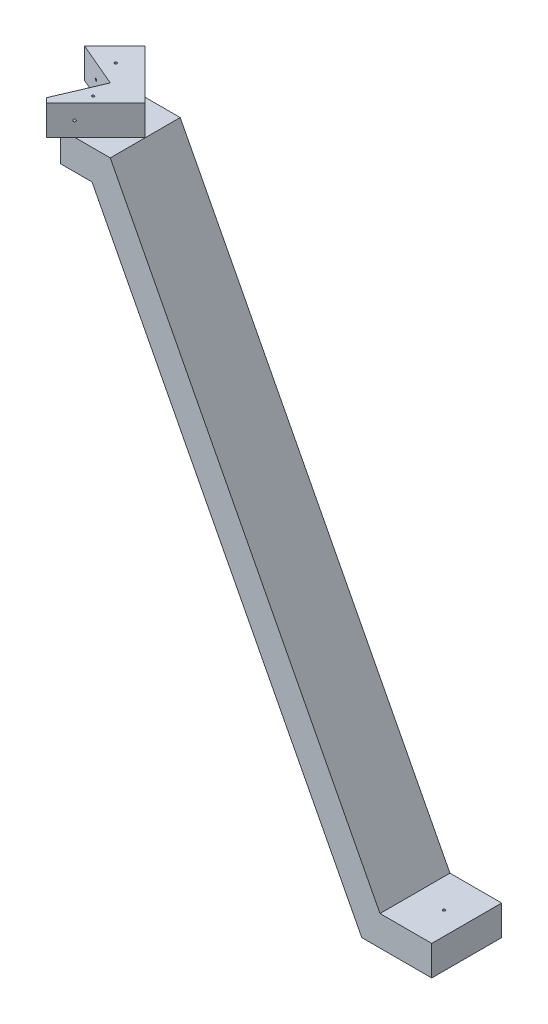
SolidWorks part; units mm, degrees
ref_plane "Frontal Plane" through (0, 0, 0) normal (0, 0, 1) x (1, 0, 0)
ref_plane "Horizontal Plane" through (0, 0, 0) normal (0, 1, 0) x (1, 0, 0)
ref_plane "Profile Plane" through (0, 0, 0) normal (1, 0, 0) x (0, 0, -1)
sketch "Sketch1" plane through (0, 0, 0) normal (0, 0, 1) x (1, 0, 0)
  line L0 (0, 0) -> (-342.9, 660.4)
  line L2 (-319.7529, 698.5) -> (23.1471, 38.1)
  line L3 (23.1471, 38.1) -> (88.9, 38.1)
  line L4 (88.9, 38.1) -> (88.9, 0)
  line L5 (88.9, 0) -> (0, 0)
  line L6 (-319.7529, 698.5) -> (-408.6529, 698.5)
  line L7 (-408.6529, 698.5) -> (-408.6529, 660.4)
  line L8 (-408.6529, 660.4) -> (-342.9, 660.4)
  dimension "D1" = 38.1
  dimension "D2" = 88.9
  dimension "D3" = 431.8
  dimension "D4" = 698.5
  dimension "D5" = 88.9
  dimension "D6" = 38.1
extrude "Boss-Extrude1" add sketch "Sketch1" along normal mid plane 88.9
hole_wizard "1/8 (0.125) Diameter Hole1" positions "3DSketch1" profile "Sketch3" hole size "1/8" standard "ANSI Inch" end condition through all
sketch3d "3DSketch1"
  line L0 (88.9, 38.1, -44.45) -> (23.1471, 38.1, -44.45) construction
  line L1 (88.9, 38.1, 44.45) -> (88.9, 38.1, -44.45) construction
  point P0 (60.1472, 38.1, 0)
  dimension "D1" = 44.45
  dimension "D2" = 28.7528
sketch "Sketch3" plane through (60.1472, 38.1, 0) normal (1, 0, 0) x (0, 0, 1)
  line L0 (0, 0) -> (0, 38.1)
  line L1 (0, 38.1) -> (1.5875, 38.1)
  line L2 (1.5875, 38.1) -> (1.5875, 0)
  line L5 (1.5875, 0) -> (0, 0)
  line L11 (0, -6.35) -> (0, 107.95) construction
  dimension "Thru Hole Dia." = 3.175
  dimension "Thru Hole Depth" = 38.1
sketch "Sketch4" plane through (0, 698.5, 0) normal (0, 1, 0) x (1, 0, 0)
  line L0 (-382.6147, 62.8618) -> (-319.7529, 0)
  line L1 (-319.7529, 0) -> (-382.6147, -62.8618)
  line L3 (-382.6147, -62.8618) -> (-445.4765, 0)
  line L4 (-445.4765, 0) -> (-382.6147, 62.8618)
  line L7 (-319.7529, 44.45) -> (-408.6529, 44.45) construction
  line L8 (-408.6529, -44.45) -> (-408.6529, 44.45) construction
  dimension "D1" = 90
  dimension "D3" = 88.9
  dimension "D4" = 44.45
  dimension "D5" = 88.9
extrude "Boss-Extrude2" add sketch "Sketch4" along normal blind 38.1
sketch "Sketch6" plane through (0, 660.4, 0) normal (0, -1, 0) x (1, 0, 0)
  line L0 (-445.4765, 190.3683) -> (-364.2029, 0)
  line L1 (-364.2029, 0) -> (-445.4765, -34.698)
  line L5 (-408.6529, 36.8236) -> (-408.6529, -36.8236) construction
  line L6 (-445.4765, 190.3683) -> (-445.4765, -34.698)
  line L7 (-408.6529, -44.45) -> (-342.9, -44.45) construction
  line L9 (-364.2029, 0) -> (-479.6244, 0) construction
  dimension "D1" = 44.45
  dimension "D2" = 44.45
  dimension "D3" = 23.119
  dimension "D4" = 115.4214
  dimension "D5" = 66.881
extrude "Cut-Extrude1" cut sketch "Sketch6" against normal through all both and the other way through all
hole_wizard "1/8 (0.125) Diameter Hole2" positions "Sketch7" profile "Sketch8" hole size "1/8" standard "ANSI Inch" end condition through all
sketch "Sketch7" plane through (-159.8765, 0, -159.8765) normal (0.7071, 0, 0.7071) x (0.7071, 0, -0.7071)
  line L0 (-314.9995, 736.6) -> (-314.9995, 698.5) construction
  line L1 (-314.9995, 698.5) -> (-288.9613, 698.5) construction
  point P0 (-289.5995, 717.55)
  dimension "D1" = 25.4
  dimension "D2" = 19.05
sketch "Sketch8" plane through (-364.6542, 717.55, 44.9013) normal (0, 1, 0) x (0.7071, 0, -0.7071)
  line L0 (0, 0) -> (0, 116.1556)
  line L1 (0, 116.1556) -> (1.5875, 116.1556)
  line L2 (1.5875, 116.1556) -> (1.5875, 0)
  line L5 (1.5875, 0) -> (0, 0)
  line L11 (0, -6.35) -> (0, 107.95) construction
  dimension "Thru Hole Dia." = 3.175
  dimension "Thru Hole Depth" = 116.1556
hole_wizard "1/8 (0.125) Diameter Hole3" positions "Sketch9" profile "Sketch10" hole size "1/8" standard "ANSI Inch" end condition through all
sketch "Sketch9" plane through (-159.8765, 0, 159.8765) normal (0.7071, 0, -0.7071) x (-0.7071, 0, -0.7071)
  line L0 (314.9995, 736.6) -> (314.9995, 698.5) construction
  line L1 (288.9613, 698.5) -> (314.9995, 698.5) construction
  point P0 (289.5995, 717.55)
  dimension "D1" = 25.4
  dimension "D2" = 19.05
sketch "Sketch10" plane through (-364.6542, 717.55, -44.9013) normal (0, 1, 0) x (-0.7071, 0, -0.7071)
  line L0 (0, 0) -> (0, 116.1556)
  line L1 (0, 116.1556) -> (1.5875, 116.1556)
  line L2 (1.5875, 116.1556) -> (1.5875, 0)
  line L5 (1.5875, 0) -> (0, 0)
  line L11 (0, -6.35) -> (0, 107.95) construction
  dimension "Thru Hole Dia." = 3.175
  dimension "Thru Hole Depth" = 116.1556
hole_wizard "1/8 (0.125) Diameter Hole4" positions "Sketch11" profile "Sketch12" hole size "1/8" standard "ANSI Inch" end condition through all
sketch "Sketch11" plane through (0, 660.4, 0) normal (0, -1, 0) x (-1, 0, 0)
  line L0 (364.2029, -44.45) -> (383.1799, -44.45) construction
  line L2 (408.6529, 44.45) -> (342.9, 44.45) construction
  line L3 (342.9, -44.45) -> (342.9, 44.45) construction
  point P0 (360.68, -25.4)
  point P2 (382.6147, 25.4)
  dimension "D1" = 19.05
  dimension "D2" = 19.05
  dimension "D4" = 17.78
sketch "Sketch12" plane through (-360.68, 660.4, 25.4) normal (1, 0, 0) x (0, 0, -1)
  line L0 (0, 0) -> (0, 76.2)
  line L1 (0, 76.2) -> (1.5875, 76.2)
  line L2 (1.5875, 76.2) -> (1.5875, 0)
  line L5 (1.5875, 0) -> (0, 0)
  line L11 (0, -6.35) -> (0, 107.95) construction
  dimension "Thru Hole Dia." = 3.175
  dimension "Thru Hole Depth" = 76.2
